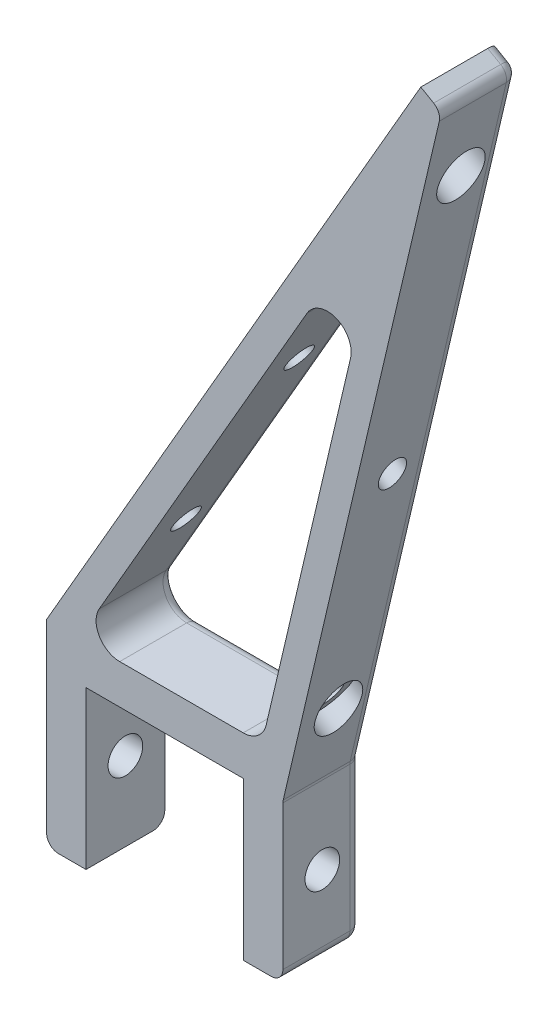
SolidWorks part; units mm, degrees
material "ABS"
ref_plane "Front Plane" through (0, 0, 0) normal (0, 0, 1) x (1, 0, 0)
ref_plane "Top Plane" through (0, 0, 0) normal (0, 1, 0) x (1, 0, 0)
ref_plane "Right Plane" through (0, 0, 0) normal (1, 0, 0) x (0, 0, -1)
sketch "Sketch1" plane through (0, 0, 0) normal (0, 0, 1) x (1, 0, 0)
  line L0 (-10, -20) -> (-10, 0)
  line L1 (-10, 0) -> (10, 0)
  line L2 (10, 0) -> (10, -20)
  line L3 (10, -20) -> (15, -20)
  line L4 (15, -20) -> (15, 0)
  line L5 (15, 0) -> (35.1015, 85.7704)
  line L6 (32.5, 87.2724) -> (-15, 5)
  line L7 (-15, 5) -> (-15, -20)
  line L8 (-15, -20) -> (-10, -20)
  line L9 (32.5, 87.2724) -> (35.1015, 85.7704)
  dimension "D1" = 5
  dimension "D2" = 20
  dimension "D3" = 20
  dimension "D4" = 166.81
  dimension "D5" = 150
  dimension "D6" = 20
  dimension "D7" = 25
  dimension "D8" = 95
extrude "Boss-Extrude1" add sketch "Sketch1" along normal blind 10
sketch "Sketch2" plane through (0, 0, 10) normal (0, 0, 1) x (1, 0, 0)
  line L0 (-10.9175, 5) -> (28.2148, 72.7791)
  line L1 (28.2148, 72.7791) -> (12.3298, 5)
  line L2 (12.3298, 5) -> (-10.9175, 5)
  line L3 (-10, 0) -> (10, 0) construction
  line L5 (15, 0) -> (35.1015, 85.7704) construction
  line L6 (32.5, 87.2724) -> (-15, 5) construction
  dimension "D1" = 5
  dimension "D2" = 3.7406
  dimension "D3" = 3.5356
extrude "Cut-Extrude1" cut sketch "Sketch2" against normal through all
fillet "Fillet1" radius 3 3 edges at (-10.9175, 5, 5) (12.3298, 5, 5) (28.2148, 72.7791, 5)
fillet "Fillet2" radius 1.5 16 edges at (35.1015, 85.7704, 5) (15, 0, 5) (15, -20, 5) (-15, -20, 5) (-8.3194, 6.5, 0) (4.8718, 32.3478, 0) (21.7651, 56.485, 0) (18.2272, 30.1633, 0) (11.8153, 5.6491, 0) (33.8007, 86.5214, 0) (25.0507, 42.8852, 0) (15, -10, 0) (12.5, -20, 0) (-15, -7.5, 0) (-12.5, -20, 0) (2.1151, 5, 0)
sketch "Sketch3" plane through (-15, 0, 0) normal (-1, 0, 0) x (0, 0, 1)
  line L0 (0, 5) -> (0, -18.5) construction
  line L1 (10, -20) -> (1.5, -20) construction
  circle A0 centre (5, -10) radius 2.2
  dimension "D1" = 5
  dimension "D2" = 10
  dimension "D3" = 4.4
extrude "Cut-Extrude2" cut sketch "Sketch3" against normal through all
sketch "Sketch4" plane through (-13.4151, 7.7452, 0) normal (-0.866, 0.5, 0) x (0, 0, 1)
  line L0 (10, 23.3264) -> (0, 23.3264) construction
  line L1 (10, 91.8301) -> (10, -3.1699) construction
  line L2 (0, 90.3301) -> (0, -0.1699) construction
  line L3 (5, 16.0989) -> (5, 23.3264) construction
  line L4 (10, 91.8301) -> (1.5, 91.8301) construction
  circle A0 centre (5, 81.3301) radius 1.75
  circle A1 centre (5, 44.8301) radius 1.75
  circle A2 centre (5, 16.0989) radius 1.75
  dimension "D1" = 3.5
  dimension "D2" = 10.5
  dimension "D3" = 36.5
  dimension "D4" = 28.7312
extrude "Cut-Extrude3" cut sketch "Sketch4" against normal through all
sketch "Sketch5" plane through (-13.4805, 7.6318, 0) normal (0.866, -0.5, 0) x (0, 0, -1)
  circle A0 centre (-5, 81.4611) radius 3
  dimension "D1" = 6
extrude "Cut-Extrude4" cut sketch "Sketch5" along normal through all from offset 3
sketch "Sketch6" plane through (-13.4151, 7.7452, 0) normal (-0.866, 0.5, 0) x (0, 0, 1)
  circle A0 centre (5, 16.0989) radius 3
  dimension "D1" = 6
extrude "Cut-Extrude5" cut sketch "Sketch6" against normal through all from offset 24.38
